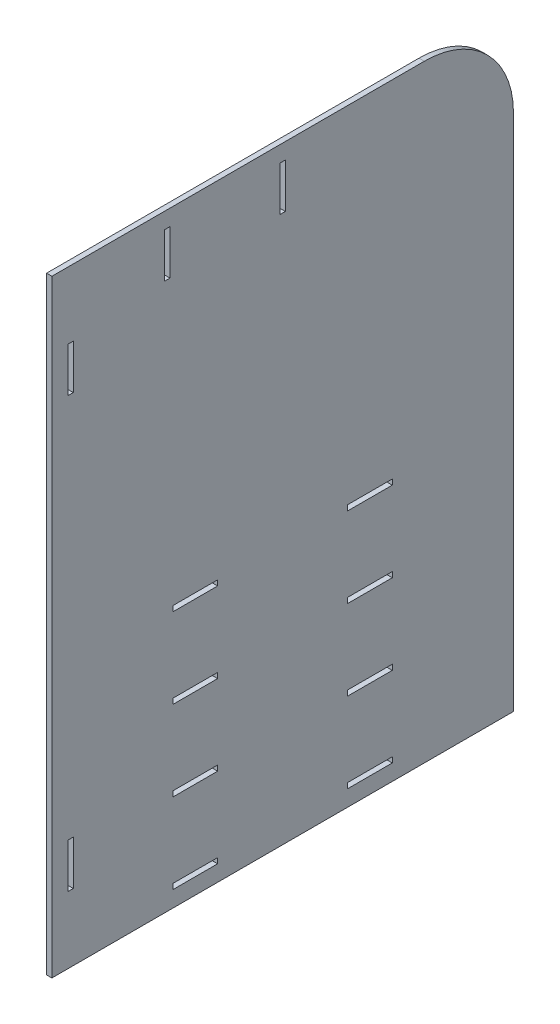
SolidWorks part; units mm, degrees
material "Maple"
ref_plane "Front Plane" through (0, 0, 0) normal (0, 0, 1) x (1, 0, 0)
ref_plane "Top Plane" through (0, 0, 0) normal (0, 1, 0) x (1, 0, 0)
ref_plane "Right Plane" through (0, 0, 0) normal (1, 0, 0) x (0, 0, -1)
sketch "Sketch1" plane through (0, 0, 0) normal (1, 0, 0) x (0, 0, -1)
  line L0 (-137.8318, 10.1512) -> (-396.8318, 10.1512) construction
  line L1 (-396.8318, 351.1512) -> (21.1682, 351.1512)
  line L2 (-396.8318, 351.1512) -> (-396.8318, -330.8488)
  line L3 (-396.8318, -330.8488) -> (121.1682, -330.8488)
  line L4 (121.1682, 251.1512) -> (121.1682, -330.8488)
  line L5 (-396.8318, 351.1512) -> (121.1682, -330.8488) construction
  line L6 (-396.8318, -330.8488) -> (121.1682, 351.1512) construction
  line L7 (-378.8318, 276.1512) -> (-372.8318, 276.1512)
  line L8 (-378.8318, 276.1512) -> (-378.8318, 226.1512)
  line L9 (-378.8318, 226.1512) -> (-372.8318, 226.1512)
  line L10 (-372.8318, 276.1512) -> (-372.8318, 226.1512)
  line L11 (-378.8318, -205.8488) -> (-372.8318, -205.8488)
  line L12 (-372.8318, -255.8488) -> (-372.8318, -205.8488)
  line L13 (-378.8318, -255.8488) -> (-372.8318, -255.8488)
  line L14 (-378.8318, -255.8488) -> (-378.8318, -205.8488)
  line L15 (-137.8318, 10.1512) -> (-137.8318, -330.8488) construction
  line L16 (-260.8318, -306.8488) -> (-210.8318, -306.8488)
  line L17 (-260.8318, -306.8488) -> (-260.8318, -312.8488)
  line L18 (-260.8318, -312.8488) -> (-210.8318, -312.8488)
  line L19 (-210.8318, -306.8488) -> (-210.8318, -312.8488)
  line L20 (-260.8318, -306.8488) -> (-210.8318, -312.8488) construction
  line L21 (-260.8318, -312.8488) -> (-210.8318, -306.8488) construction
  line L22 (-14.8318, -312.8488) -> (-64.8318, -312.8488)
  line L23 (-64.8318, -306.8488) -> (-64.8318, -312.8488)
  line L24 (-14.8318, -306.8488) -> (-64.8318, -306.8488)
  line L25 (-14.8318, -306.8488) -> (-14.8318, -312.8488)
  line L26 (-260.8318, -216.8488) -> (-260.8318, -222.8488)
  line L27 (-260.8318, -216.8488) -> (-210.8318, -216.8488)
  line L28 (-210.8318, -216.8488) -> (-210.8318, -222.8488)
  line L29 (-260.8318, -222.8488) -> (-210.8318, -222.8488)
  line L30 (-14.8318, -222.8488) -> (-64.8318, -222.8488)
  line L31 (-64.8318, -216.8488) -> (-64.8318, -222.8488)
  line L32 (-14.8318, -216.8488) -> (-64.8318, -216.8488)
  line L33 (-14.8318, -216.8488) -> (-14.8318, -222.8488)
  line L34 (-260.8318, -126.8488) -> (-260.8318, -132.8488)
  line L35 (-260.8318, -126.8488) -> (-210.8318, -126.8488)
  line L36 (-210.8318, -126.8488) -> (-210.8318, -132.8488)
  line L37 (-260.8318, -132.8488) -> (-210.8318, -132.8488)
  line L38 (-14.8318, -132.8488) -> (-64.8318, -132.8488)
  line L39 (-64.8318, -126.8488) -> (-64.8318, -132.8488)
  line L40 (-14.8318, -126.8488) -> (-64.8318, -126.8488)
  line L41 (-14.8318, -126.8488) -> (-14.8318, -132.8488)
  line L42 (-260.8318, -36.8488) -> (-260.8318, -42.8488)
  line L43 (-260.8318, -36.8488) -> (-210.8318, -36.8488)
  line L44 (-210.8318, -36.8488) -> (-210.8318, -42.8488)
  line L45 (-260.8318, -42.8488) -> (-210.8318, -42.8488)
  line L46 (-14.8318, -42.8488) -> (-64.8318, -42.8488)
  line L47 (-64.8318, -36.8488) -> (-64.8318, -42.8488)
  line L48 (-14.8318, -36.8488) -> (-64.8318, -36.8488)
  line L49 (-14.8318, -36.8488) -> (-14.8318, -42.8488)
  line L50 (-137.8318, 10.1512) -> (-137.8318, 351.1512) construction
  line L51 (-396.8318, 308.1512) -> (-137.8318, 308.1512) construction
  line L52 (-267.3318, 308.1512) -> (-267.3318, 344.969) construction
  line L54 (-270.3318, 333.1512) -> (-264.3318, 333.1512)
  line L55 (-270.3318, 333.1512) -> (-270.3318, 283.1512)
  line L56 (-270.3318, 283.1512) -> (-264.3318, 283.1512)
  line L57 (-264.3318, 333.1512) -> (-264.3318, 283.1512)
  line L58 (-270.3318, 333.1512) -> (-264.3318, 283.1512) construction
  line L59 (-270.3318, 283.1512) -> (-264.3318, 333.1512) construction
  line L60 (-140.8318, 333.1512) -> (-134.8318, 333.1512)
  line L61 (-140.8318, 333.1512) -> (-140.8318, 283.1512)
  line L62 (-140.8318, 283.1512) -> (-134.8318, 283.1512)
  line L63 (-134.8318, 333.1512) -> (-134.8318, 283.1512)
  line L64 (-140.8318, 333.1512) -> (-134.8318, 283.1512) construction
  line L65 (-140.8318, 283.1512) -> (-134.8318, 333.1512) construction
  arc A0 (121.1682, 251.1512) -> (21.1682, 351.1512) centre (21.1682, 251.1512) ccw
  point P0 (-137.8318, 10.1512)
  point P18 (-235.8318, -309.8488)
  dimension "D3" = 100
  dimension "D1" = 682
  dimension "D2" = 518
  dimension "D4" = 75
  dimension "D5" = 18
  dimension "D6" = 6
  dimension "D7" = 50
  dimension "D8" = 18
  dimension "D9" = 136
  dimension "D10" = 50
  dimension "D11" = 6
  dimension "D13" = 18
  dimension "D14" = 6
  dimension "D15" = 50
  dimension "D16" = 6
  dimension "D17" = 50
  dimension "D18" = 18
  dimension "D20" = 50
  dimension "D21" = 75
  dimension "D12" = 4
extrude "Boss-Extrude1" add sketch "Sketch1" along normal blind 6
